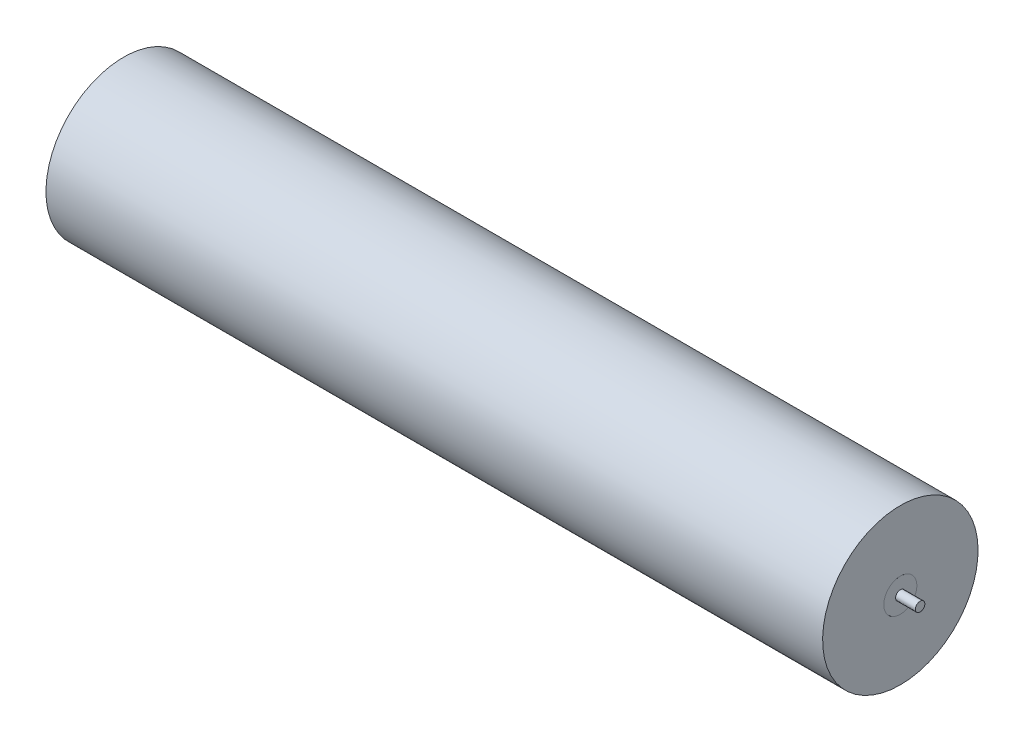
SolidWorks part; units mm, degrees
material "AISI 304"
ref_plane "Front Plane" through (0, 0, 0) normal (0, 0, 1) x (1, 0, 0)
ref_plane "Top Plane" through (0, 0, 0) normal (0, 1, 0) x (1, 0, 0)
ref_plane "Right Plane" through (0, 0, 0) normal (1, 0, 0) x (0, 0, -1)
sketch "Sketch1" plane through (0, 0, 0) normal (0, 0, 1) x (1, 0, 0)
  line L0 (-824.5, 165) -> (824.5, 165)
  line L1 (824.5, 165) -> (824.5, 35.1005)
  line L2 (824.5, 35.1005) -> (-824.5, 35.1005)
  line L3 (-824.5, 35.1005) -> (-824.5, 165)
  line L4 (-824.5, 0) -> (824.5, 0) construction
  point P8 (0, 0)
  dimension "D1" = 1649
  dimension "D2" = 330
  dimension "D3" = 70.201
revolve "Revolve1" add sketch "Sketch1" angle 360 about L4
sketch "Sketch2" plane through (-824.5, 0, 0) normal (-1, 0, 0) x (0, 0, 1)
  circle A1 centre (0, 0) radius 35.1
  circle A2 centre (0, 0) radius 10.0005
  dimension "D1" = 20.001
  dimension "D2" = 70.2
extrude "Boss-Extrude1" add sketch "Sketch2" against normal blind 10
sketch "Sketch3" plane through (824.5, 0, 0) normal (1, 0, 0) x (0, 0, -1)
  circle A0 centre (0, 0) radius 10.0005 construction
  circle A1 centre (0, 0) radius 35.1
  circle A2 centre (0, 0) radius 35.1
  circle A3 centre (0, 0) radius 10.0005
  dimension "D1" = 0
extrude "Boss-Extrude2" add sketch "Sketch3" against normal blind 10 separate body
sketch "Sketch4" plane through (0, 0, 0) normal (0, 0, 1) x (1, 0, 0)
  line L0 (-866.5, 10) -> (866.5, 10)
  line L1 (-824.5, 10.0005) -> (-824.5, -10.0005) construction
  line L6 (866.5, 0) -> (-866.5, 0) construction
  line L8 (-824.5, 10.0005) -> (-824.5, -10.0005) construction
  line L9 (-866.5, 10) -> (-866.5, 0)
  line L10 (-866.5, 0) -> (866.5, 0) construction
  line L11 (-866.5, 0) -> (866.5, 0)
  line L14 (866.5, 10) -> (866.5, 0)
  line L17 (-824.5, 35.1) -> (-824.5, -35.1) construction
  line L18 (824.5, -35.1) -> (824.5, 35.1) construction
  point P17 (866.5, 5)
  dimension "D2" = 42
  dimension "D5" = 42
  dimension "D7" = 20
revolve "Revolve3" add sketch "Sketch4" angle 360 about L11
